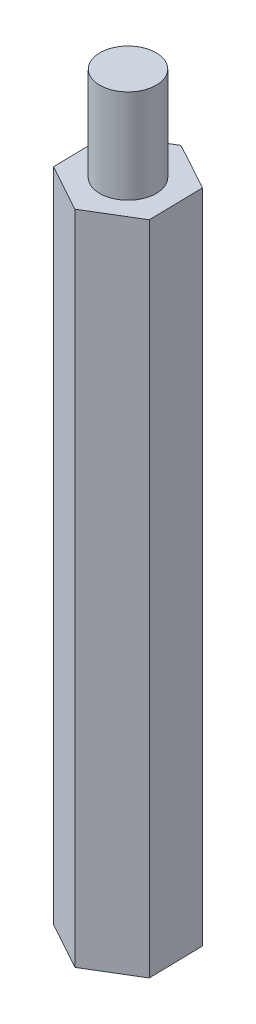
SolidWorks part; units mm, degrees
ref_plane "前视基准面" through (0, 0, 0) normal (0, 0, 1) x (1, 0, 0)
ref_plane "上视基准面" through (0, 0, 0) normal (0, 1, 0) x (1, 0, 0)
ref_plane "右视基准面" through (0, 0, 0) normal (1, 0, 0) x (0, 0, -1)
sketch "草图1" plane through (0, 0, 0) normal (0, 1, 0) x (1, 0, 0)
  line L1 (2.5283, -1.3932) -> (2.4707, 1.493)
  line L2 (2.4707, 1.493) -> (-0.0577, 2.8862)
  line L3 (-0.0577, 2.8862) -> (-2.5283, 1.3932)
  line L4 (-2.5283, 1.3932) -> (-2.4707, -1.493)
  line L5 (-2.4707, -1.493) -> (0.0577, -2.8862)
  line L6 (0.0577, -2.8862) -> (2.5283, -1.3932)
  circle A0 centre (0, 0) radius 2.5 construction
  dimension "D1" = 5
extrude "凸台-拉伸1" add sketch "草图1" along normal blind 35
sketch "草图2" plane through (0, 0, 0) normal (0, -1, 0) x (1, 0, 0)
  circle A0 centre (0, 0) radius 1.5
  dimension "D1" = 3
extrude "切除-拉伸1" cut sketch "草图2" against normal blind 5
sketch "草图3" plane through (0, 35, 0) normal (0, 1, 0) x (1, 0, 0)
  circle A0 centre (0, 0) radius 1.5
  dimension "D1" = 3
extrude "凸台-拉伸2" add sketch "草图3" along normal blind 5
